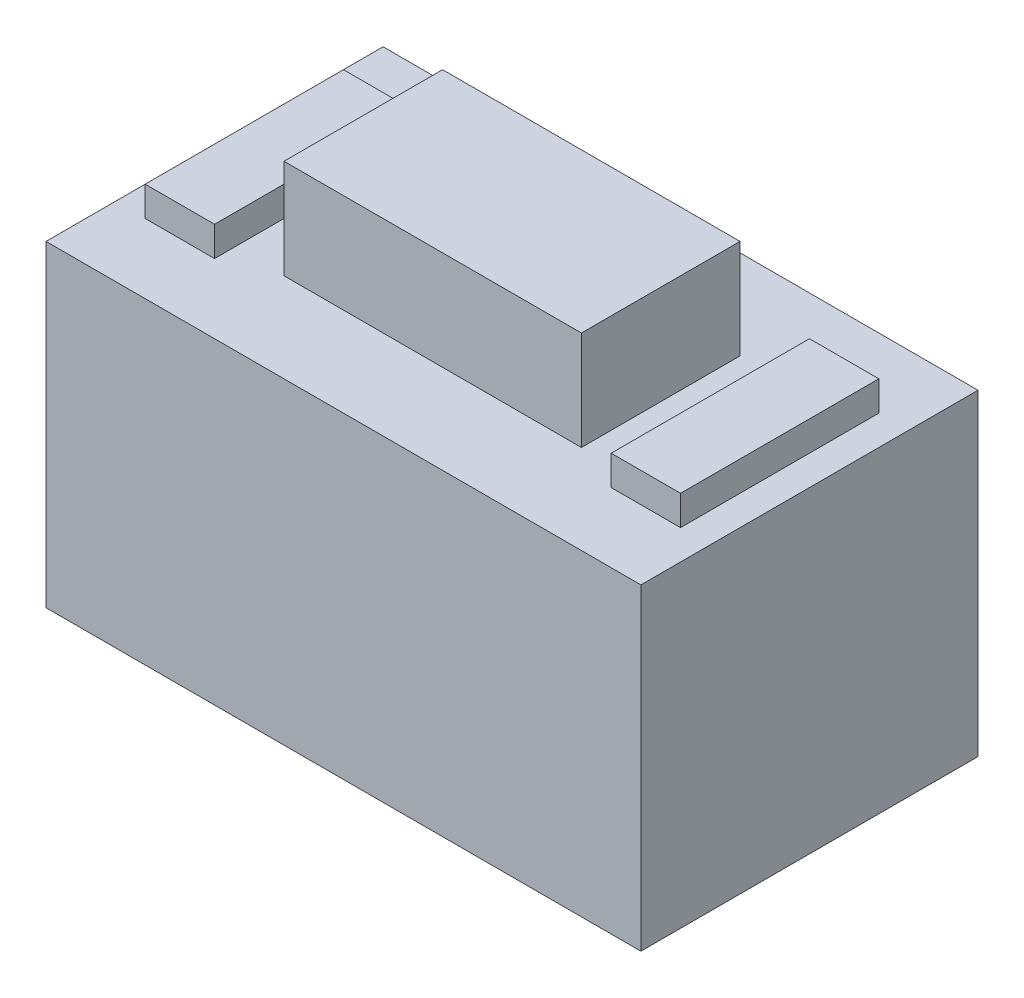
SolidWorks part; units mm, degrees
ref_plane "Přední rovina" through (0, 0, 0) normal (0, 0, 1) x (1, 0, 0)
ref_plane "Horní rovina" through (0, 0, 0) normal (0, 1, 0) x (1, 0, 0)
ref_plane "Pravá rovina" through (0, 0, 0) normal (1, 0, 0) x (0, 0, -1)
sketch "Skica1" plane through (0, 0, 0) normal (0, 0, 1) x (1, 0, 0)
  line L1 (-3, -1.6) -> (3, -1.6)
  line L2 (-3, -1.6) -> (-3, 1.6)
  line L3 (-3, 1.6) -> (3, 1.6)
  line L4 (3, -1.6) -> (3, 1.6)
  line L5 (-3, -1.6) -> (3, 1.6) construction
  line L6 (-3, 1.6) -> (3, -1.6) construction
  point P0 (0, 0)
  dimension "D1" = 3.2
  dimension "D2" = 6
extrude "Přidat vysunutím1" add sketch "Skica1" along normal blind 3.4
sketch "Skica2" plane through (0, 1.6, 0) normal (0, 1, 0) x (1, 0, 0)
  line L0 (0, 0) -> (0, -3.4) construction
  line L1 (3, 0) -> (-3, 0) construction
  line L2 (3, -3.4) -> (-3, -3.4) construction
  line L3 (0, -3.4) -> (-3, -1.7) construction
  line L4 (-3, -3.4) -> (-3, 0) construction
  line L5 (-3, -1.7) -> (3, -1.7) construction
  line L6 (3, -3.4) -> (3, 0) construction
  line L8 (-1.5, -2.5) -> (1.5, -2.5)
  line L9 (-1.5, -2.5) -> (-1.5, -0.9)
  line L10 (-1.5, -0.9) -> (1.5, -0.9)
  line L11 (1.5, -2.5) -> (1.5, -0.9)
  line L12 (-1.5, -2.5) -> (1.5, -0.9) construction
  line L13 (-1.5, -0.9) -> (1.5, -2.5) construction
  point P6 (0, -1.7)
  dimension "D1" = 3
  dimension "D2" = 1.6
extrude "Přidat vysunutím2" add sketch "Skica2" along normal blind 1
sketch "Skica3" plane through (0, 1.6, 0) normal (0, 1, 0) x (1, 0, 0)
  line L0 (3, -3.4) -> (-3, -3.4) construction
  line L1 (-2, -0.7) -> (-2.7, -0.7)
  line L2 (-2, -0.7) -> (-2, -2.7)
  line L3 (-2, -2.7) -> (-2.7, -2.7)
  line L4 (-2.7, -0.7) -> (-2.7, -2.7)
  line L5 (-2, -0.7) -> (-2.7, -2.7) construction
  line L6 (-2, -2.7) -> (-2.7, -0.7) construction
  line L7 (3, 0) -> (-3, 0) construction
  line L8 (0, 0.7582) -> (0, -5.9545) construction
  line L9 (-1.5, -0.9) -> (-1.5, -2.5) construction
  line L11 (2.7, -0.7) -> (2.7, -2.7)
  line L12 (2, -0.7) -> (2, -2.7)
  line L13 (2.7, -2.7) -> (2, -2.7)
  line L14 (2.7, -0.7) -> (2, -0.7)
  line L15 (2.7, -0.7) -> (2, -2.7) construction
  line L16 (2.7, -2.7) -> (2, -0.7) construction
  line L19 (3, -3.4) -> (3, 0) construction
  point P0 (-2.35, -1.7)
  dimension "D1" = 0.7
  dimension "D2" = 2
  dimension "D3" = 0.7
  dimension "D4" = 0.7
  dimension "D5" = 0.5
  dimension "D6" = 2
extrude "Přidat vysunutím3" add sketch "Skica3" along normal blind 0.3
